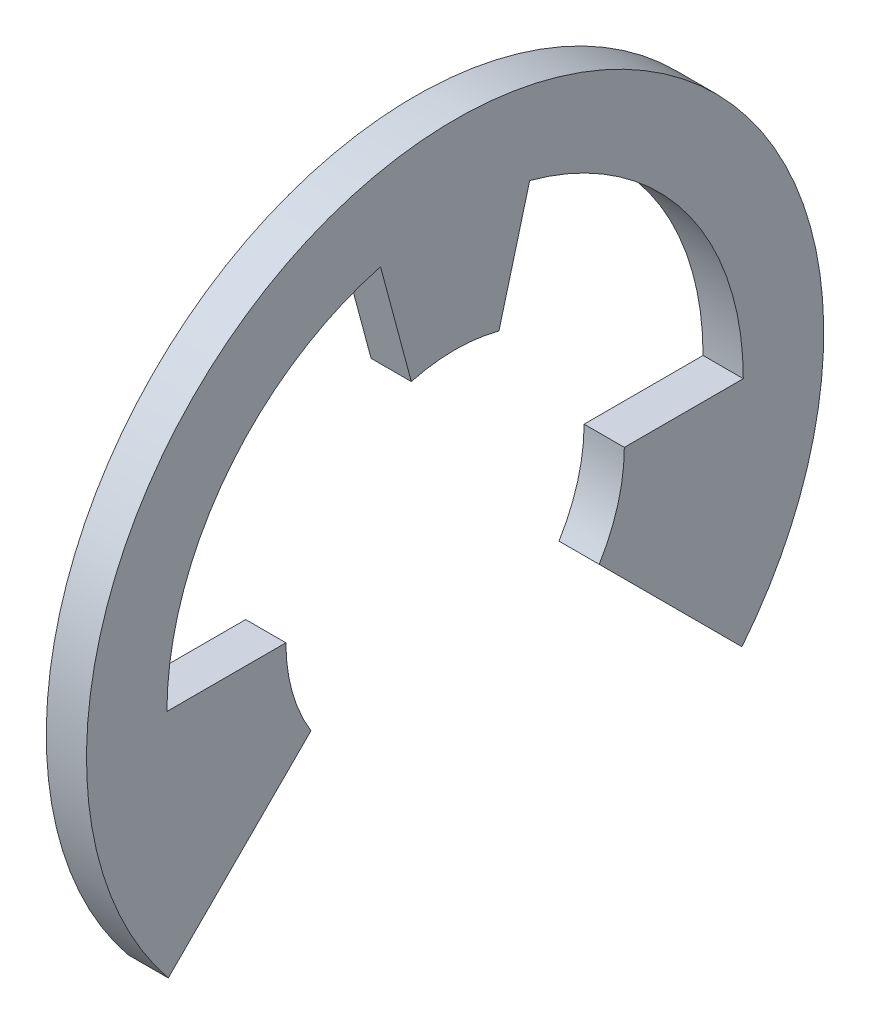
SolidWorks part; units mm, degrees
ref_plane "Front Plane" through (0, 0, 0) normal (0, 0, 1) x (1, 0, 0)
ref_plane "Top Plane" through (0, 0, 0) normal (0, 1, 0) x (1, 0, 0)
ref_plane "Right Plane" through (0, 0, 0) normal (1, 0, 0) x (0, 0, -1)
sketch "Sketch1" plane through (0, 0, 0) normal (1, 0, 0) x (0, 0, -1)
  line L0 (-2.525, 0) -> (-4.3, 0)
  line L1 (-0.6535, 2.439) -> (-1.1129, 4.1535)
  line L2 (2.525, 0) -> (4.3, 0)
  line L3 (1.1129, 4.1535) -> (0.6535, 2.439)
  line L4 (-2.15, -1.3241) -> (-4.2801, -3.4541)
  line L5 (2.15, -1.3241) -> (4.2801, -3.4541)
  line L9 (0, 0) -> (0, 5.5) construction
  arc A0 (-2.525, 0) -> (-2.15, -1.3241) centre (0, 0) ccw
  arc A1 (4.2801, -3.4541) -> (-4.2801, -3.4541) centre (0, 0) ccw
  arc A2 (4.3, 0) -> (1.1129, 4.1535) centre (0, 0) ccw
  arc A3 (0.6535, 2.439) -> (-0.6535, 2.439) centre (0, 0) ccw
  arc A4 (-1.1129, 4.1535) -> (-4.3, 0) centre (0, 0) ccw
  arc A5 (2.15, -1.3241) -> (2.525, 0) centre (0, 0) ccw
  circle A6 centre (0, 0) radius 2.525 construction
  dimension "D1" = 30
  dimension "D2" = 90
  dimension "REE_D" = 11
  dimension "REE_D_s" = 5.05
  dimension "REE_B_s" = 1.2
  dimension "REE_H" = 4.3
extrude "Boss-Extrude1" add sketch "Sketch1" along normal blind 0.6
